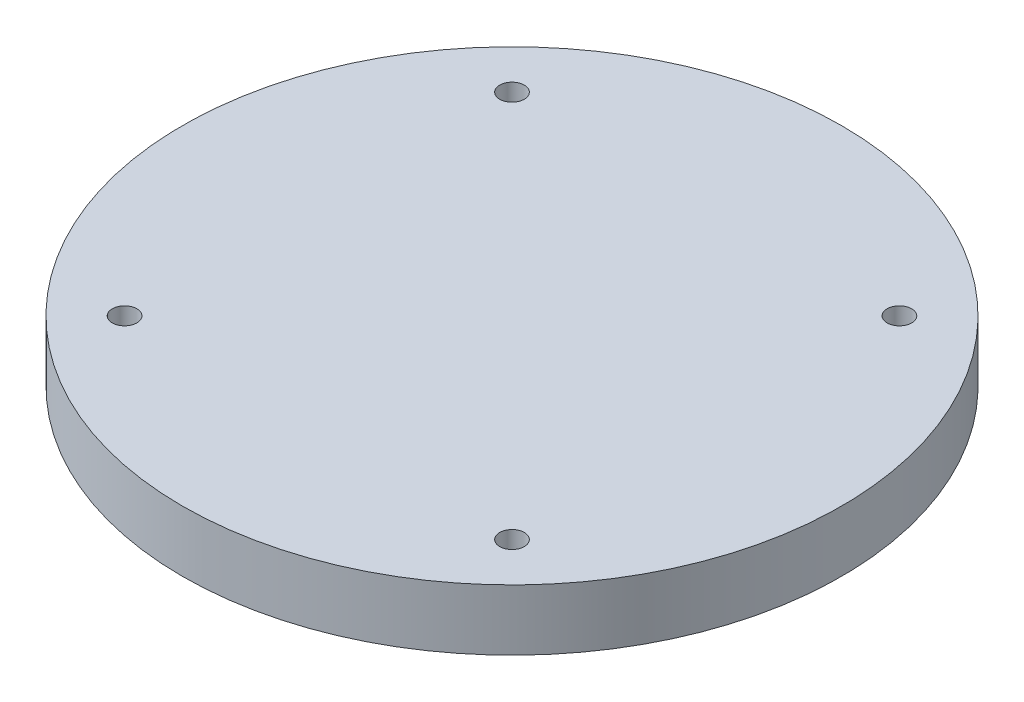
SolidWorks part; units mm, degrees
ref_plane "Front Plane" through (0, 0, 0) normal (0, 0, 1) x (1, 0, 0)
ref_plane "Top Plane" through (0, 0, 0) normal (0, 1, 0) x (1, 0, 0)
ref_plane "Right Plane" through (0, 0, 0) normal (1, 0, 0) x (0, 0, -1)
sketch "Sketch1" plane through (0, 0, 0) normal (0, 1, 0) x (1, 0, 0)
  circle A0 centre (0, 0) radius 27.5
  dimension "D1" = 55
extrude "Boss-Extrude1" add sketch "Sketch1" along normal blind 5.08
sketch "Sketch2" plane through (0, 5.08, 0) normal (0, 1, 0) x (1, 0, 0)
  line L0 (0, 0) -> (16.1645, 16.1645)
  circle A0 centre (16.1645, 16.1645) radius 1.025
  circle A1 centre (16.1645, -16.1645) radius 1.025
  circle A2 centre (-16.1645, -16.1645) radius 1.025
  circle A3 centre (-16.1645, 16.1645) radius 1.025
  point P13 (0, 0)
  dimension "D2" = 2.05
  dimension "D1" = 22.86
  dimension "D3" = 4
extrude "Cut-Extrude1" cut sketch "Sketch2" against normal blind 3.175
